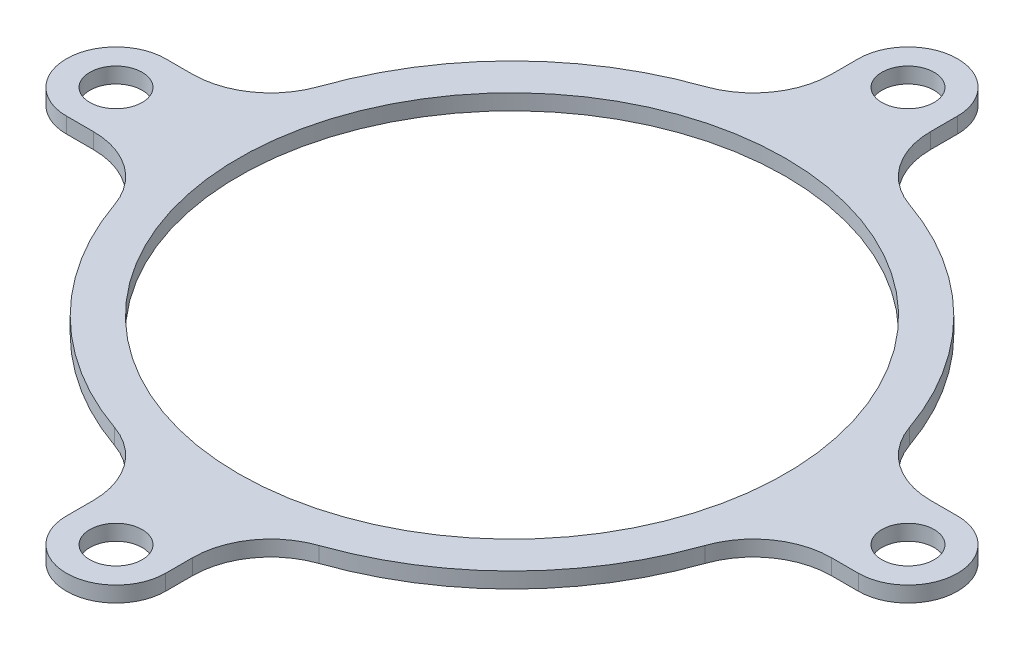
SolidWorks part; units mm, degrees
ref_plane "Front Plane" through (0, 0, 0) normal (0, 0, 1) x (1, 0, 0)
ref_plane "Top Plane" through (0, 0, 0) normal (0, 1, 0) x (1, 0, 0)
ref_plane "Right Plane" through (0, 0, 0) normal (1, 0, 0) x (0, 0, -1)
sketch "Sketch1" plane through (0, 0, 0) normal (0, 1, 0) x (1, 0, 0)
  circle A0 centre (0, 0) radius 35
  circle A1 centre (0, 0) radius 40
  dimension "innerDiam" = 70
  dimension "outerDiam" = 80
extrude "Boss-Extrude1" add sketch "Sketch1" along normal mid plane 2
sketch "Sketch2" plane through (0, 1, 0) normal (0, 1, 0) x (1, 0, 0)
  line L0 (0, 0) -> (0, 38.8704) construction
  line L1 (-6.35, 47.2512) -> (-6.35, 50.7)
  line L2 (6.35, 50.7) -> (6.35, 47.2512)
  arc A0 (-6.35, 50.7) -> (6.35, 50.7) centre (0, 50.7) cw
  arc A1 (6.35, 47.2512) -> (13.08, 37.801) centre (16.35, 47.2512) ccw
  circle A2 centre (0, 0) radius 40 construction
  arc A3 (-6.35, 47.2512) -> (-13.08, 37.801) centre (-16.35, 47.2512) cw
  arc A4 (13.08, 37.801) -> (-13.08, 37.801) centre (0, 0) ccw
  circle A5 centre (0, 0) radius 50.7 construction
  circle A6 centre (0, 50.7) radius 3.35
  dimension "supportsDiam" = 101.4
  dimension "rodDiam" = 6.7
  dimension "D3" = 3
  dimension "D4" = 10
extrude "Boss-Extrude2" add sketch "Sketch2" against normal up to surface (2 mm away) up to face at (0, -1, 40)
pattern_circular "CirPattern1" count 4 over 360 about axis through (0, 0, 0) along (0, 1, 0) of "Boss-Extrude2"
